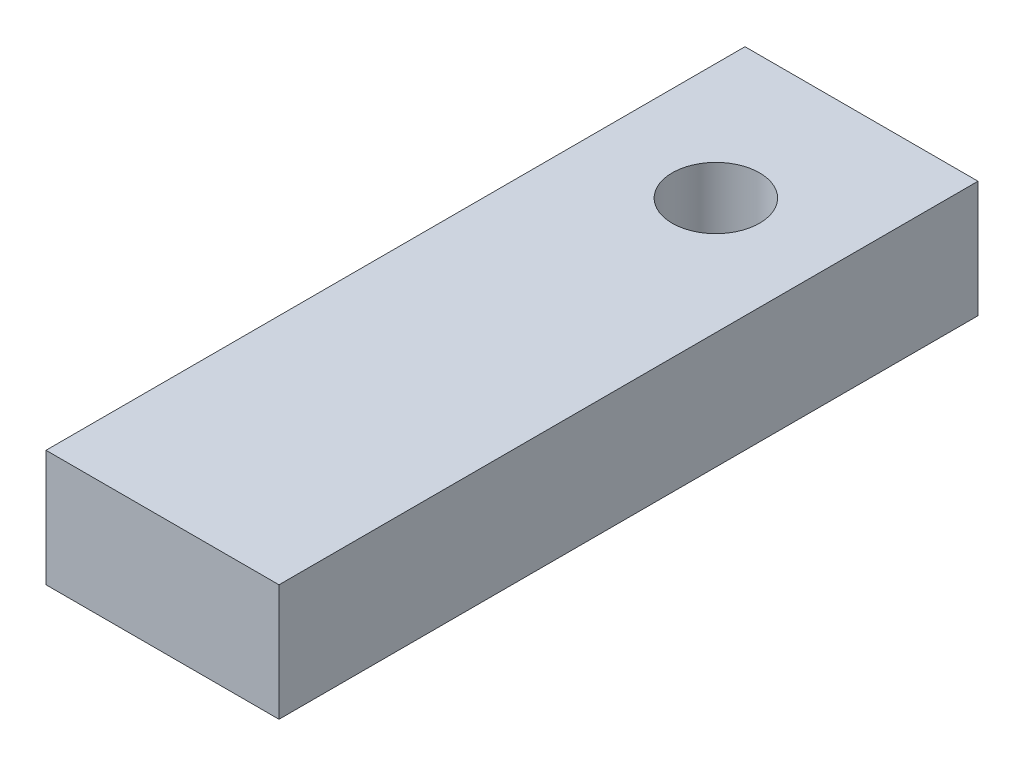
SolidWorks part; units mm, degrees
ref_plane "Front Plane" through (0, 0, 0) normal (0, 0, 1) x (1, 0, 0)
ref_plane "Top Plane" through (0, 0, 0) normal (0, 1, 0) x (1, 0, 0)
ref_plane "Right Plane" through (0, 0, 0) normal (1, 0, 0) x (0, 0, -1)
sketch "Sketch1" plane through (0, 0, 0) normal (0, 0, 1) x (1, 0, 0)
  line L1 (-50.8, -25.4) -> (50.8, -25.4)
  line L2 (-50.8, -25.4) -> (-50.8, 25.4)
  line L3 (-50.8, 25.4) -> (50.8, 25.4)
  line L4 (50.8, -25.4) -> (50.8, 25.4)
  line L5 (-50.8, -25.4) -> (50.8, 25.4) construction
  line L6 (-50.8, 25.4) -> (50.8, -25.4) construction
  point P0 (0, 0)
  dimension "D1" = 50.8
  dimension "D2" = 101.6
extrude "Boss-Extrude1" add sketch "Sketch1" along normal blind 304.8
sketch "Sketch2" plane through (0, 25.4, 0) normal (0, 1, 0) x (1, 0, 0)
  line L0 (0, 0) -> (0, -63.5) construction
  circle A0 centre (0, -63.5) radius 19.05
  point P4 (0, 0)
  dimension "D2" = 38.1
  dimension "D1" = 63.5
extrude "Cut-Extrude1" cut sketch "Sketch2" against normal through all
